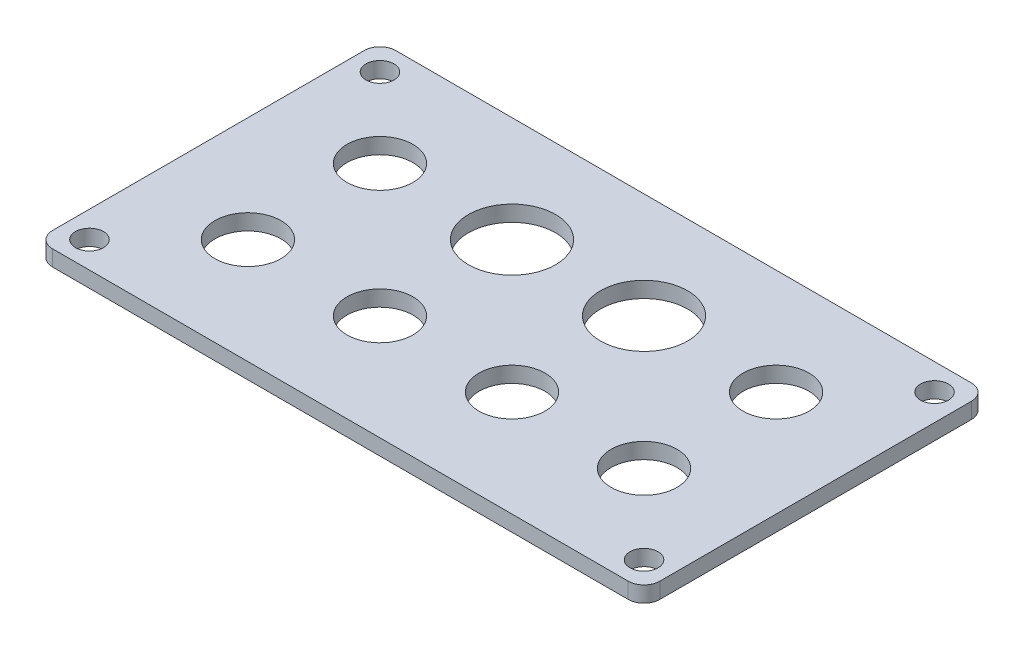
SolidWorks part; units mm, degrees
ref_plane "Front Plane" through (0, 0, 0) normal (0, 0, 1) x (1, 0, 0)
ref_plane "Top Plane" through (0, 0, 0) normal (0, 1, 0) x (1, 0, 0)
ref_plane "Right Plane" through (0, 0, 0) normal (1, 0, 0) x (0, 0, -1)
sketch "Sketch1" plane through (0, 0, 0) normal (0, 1, 0) x (1, 0, 0)
  line L1 (0, 0) -> (115, 0)
  line L2 (0, 0) -> (0, 65)
  line L3 (0, 65) -> (115, 65)
  line L4 (115, 0) -> (115, 65)
  dimension "D1" = 115
  dimension "D2" = 65
extrude "Boss-Extrude1" add sketch "Sketch1" along normal blind 3
sketch "Sketch2" plane through (0, 3, 0) normal (0, 1, 0) x (1, 0, 0)
  line L0 (0, 65) -> (0, 0) construction
  line L1 (0, 0) -> (115, 0) construction
  circle A0 centre (20, 20) radius 6.25
  dimension "D3" = 12.5
  dimension "D1" = 20
  dimension "D2" = 20
extrude "Cut-Extrude1" cut sketch "Sketch2" against normal up to surface (3 mm away) up to face at (57.5, 0, -32.5)
pattern_linear "LPattern1" count 4 spacing 25 along (1, 0, 0) count 2 spacing 25 along (0, 0, -1) skipping (1, 1), (2, 1) of "Cut-Extrude1"
sketch "Sketch3" plane through (0, 3, 0) normal (0, 1, 0) x (1, 0, 0)
  line L0 (45, 20) -> (70, 20) construction
  line L1 (57.5, 20) -> (57.5, 45) construction
  line L2 (70, 45) -> (45, 45) construction
  circle A0 centre (45, 45) radius 8.25
  circle A1 centre (70, 45) radius 8.25
  point P8 (20, 45)
  point P14 (57.5, 45)
  dimension "D1" = 16.5
extrude "Cut-Extrude2" cut sketch "Sketch3" against normal up to surface (3 mm away) up to face at (45, 0, -26.25)
hole_wizard "M5 Clearance Hole1" positions "Sketch4" profile "Sketch5" hole size "M5" standard "ANSI Metric" end condition up to next
sketch "Sketch4" plane through (0, 3, 0) normal (0, 1, 0) x (1, 0, 0)
  line L12 (5, 60) -> (5, 5)
  line L13 (5, 5) -> (110, 5)
  line L14 (110, 5) -> (110, 60)
  line L15 (110, 60) -> (5, 60)
  line L16 (5, 60) -> (5, 5)
  line L17 (5, 5) -> (110, 5)
  line L18 (110, 5) -> (110, 60)
  line L19 (110, 60) -> (5, 60)
  point P25 (5, 60)
  point P26 (5, 5)
  point P27 (110, 5)
  point P28 (110, 60)
  dimension "D1" = 5
sketch "Sketch5" plane through (5, 3, -60) normal (1, 0, 0) x (0, 0, 1)
  line L0 (0, 0) -> (0, 3)
  line L1 (0, 3) -> (2.65, 3)
  line L2 (2.65, 3) -> (2.65, 0)
  line L5 (2.65, 0) -> (0, 0)
  line L11 (0, -6.35) -> (0, 107.95) construction
  dimension "Thru Hole Dia." = 5.3
  dimension "Thru Hole Depth" = 3
fillet "Fillet1" radius 3 4 edges at (115, 1.5, -65) (115, 1.5, 0) (0, 1.5, 0) (0, 1.5, -65)
